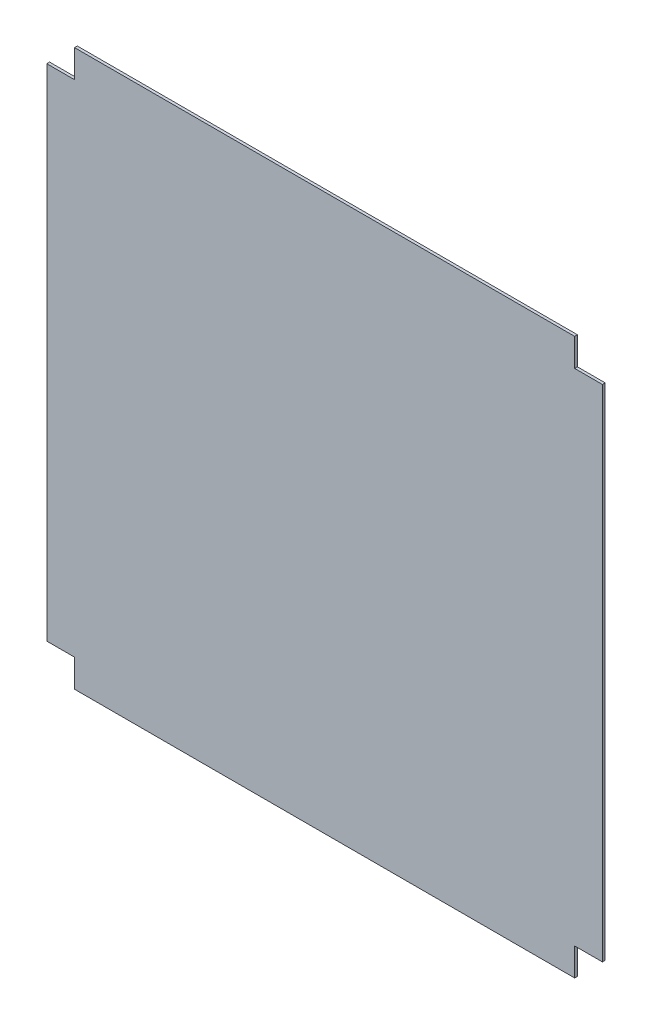
SolidWorks part; units mm, degrees
material "6063-T1"
ref_plane "Front Plane" through (0, 0, 0) normal (1, 0, 0) x (0, 1, 0)
ref_plane "Top Plane" through (0, 0, 0) normal (0, 0, 1) x (0, 1, 0)
ref_plane "Right Plane" through (0, 0, 0) normal (0, 1, 0) x (-1, 0, 0)
sketch "Sketch1" plane through (0, 0, 0) normal (0, 0, 1) x (0, 1, 0)
  line L0 (380, 0) -> (400, 0)
  line L1 (0, 0) -> (400, 0)
  line L2 (0, 0) -> (0, -400)
  line L3 (0, -400) -> (400, -400)
  line L4 (400, 0) -> (400, -400)
  line L5 (0, 0) -> (20, 0)
  line L6 (0, 0) -> (0, -20)
  line L7 (0, -20) -> (20, -20)
  line L8 (20, 0) -> (20, -20)
  line L9 (380, 0) -> (380, -20)
  line L10 (380, -20) -> (400, -20)
  line L11 (400, 0) -> (400, -20)
  line L12 (380, -380) -> (400, -380)
  line L13 (380, -380) -> (380, -400)
  line L14 (380, -400) -> (400, -400)
  line L15 (400, -380) -> (400, -400)
  line L16 (0, -380) -> (20, -380)
  line L17 (0, -380) -> (0, -400)
  line L18 (0, -400) -> (20, -400)
  line L19 (20, -380) -> (20, -400)
  line L20 (0, 0) -> (380, 0) construction
  line L21 (0, 0) -> (0, -380) construction
  dimension "D1" = 400
  dimension "D2" = 400
  dimension "D4" = 20
  dimension "D3" = 20
  dimension "D7" = 380
  dimension "D8" = 380
  dimension "D5" = 2
  dimension "D6" = 2
extrude "Boss-Extrude1" add sketch "Sketch1" along normal blind 2 contours L16 L19 L3 L13 L12 L4 L10 L9 L1 L8 L7 L2
equation "\"extrusion_width\"= 20mm'assuming we are using square beams"
equation "\"frame_height\"= 400mm'vertical height of the printer"
equation "\"frame_width\"= 400mm"
equation "\"frame_length\"= 400mm"
equation "\"D1@Sketch1\"=\"frame_length\""
equation "\"D2@Sketch1\"=\"frame_width\""
equation "\"D3@Sketch1\"=\"extrusion_width\""
equation "\"D7@Sketch1\"=\"frame_length\"-\"extrusion_width\""
equation "\"D8@Sketch1\"=\"frame_width\"-\"extrusion_width\""
equation "\"base_platform_thickness\"= 2mm'depends on sheet metal"
equation "\"D1@Boss-Extrude1\"=\"base_platform_thickness\""
